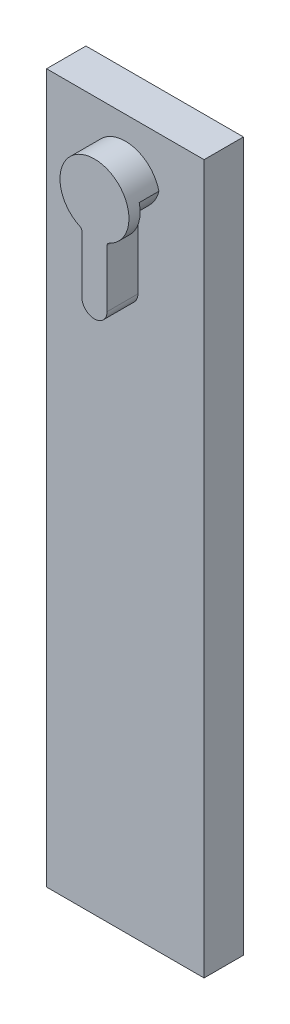
SolidWorks part; units mm, degrees
material "ASA"
ref_plane "Front Plane" through (0, 0, 0) normal (0, 0, 1) x (1, 0, 0)
ref_plane "Top Plane" through (0, 0, 0) normal (0, 1, 0) x (1, 0, 0)
ref_plane "Right Plane" through (0, 0, 0) normal (1, 0, 0) x (0, 0, -1)
sketch "Sketch1" plane through (0, 0, 0) normal (0, 0, 1) x (1, 0, 0)
  line L1 (0, 0) -> (25.4, 0)
  line L2 (0, 0) -> (0, 114.3)
  line L3 (0, 114.3) -> (25.4, 114.3)
  line L4 (25.4, 0) -> (25.4, 114.3)
  dimension "D1" = 25.4
  dimension "D2" = 114.3
extrude "Boss-Extrude1" add sketch "Sketch1" against normal blind 6.35
sketch "Sketch2" plane through (0, 0, 0) normal (0, 0, 1) x (1, 0, 0)
  line L0 (25.4, 114.3) -> (0, 114.3) construction
  line L1 (0, 114.3) -> (0, 0) construction
  circle A0 centre (12.7, 107.5182) radius 5.5626
  circle A1 centre (12.7, 107.5182) radius 6.0706 construction
  dimension "D3" = 0.508
  dimension "D4" = 12.1412
  dimension "D1" = 6.7818
  dimension "D2" = 12.7
extrude "Boss-Extrude2" add sketch "Sketch2" along normal blind 3.175
sketch "Sketch3" plane through (0, 0, 3.175) normal (0, 0, 1) x (1, 0, 0)
  line L0 (12.7, 107.5182) -> (12.7, 104.9782) construction
  circle A0 centre (12.7, 104.9782) radius 5.5626
  circle A2 centre (12.7, 107.5182) radius 5.5626 construction
  dimension "D1" = 2.54
extrude "Boss-Extrude3" add sketch "Sketch3" along normal blind 1.8
sketch "Sketch4" plane through (0, 0, 0) normal (0, 0, 1) x (1, 0, 0)
  line L0 (12.7, 107.5182) -> (12.7, 90.2208) construction
  line L1 (15.24, 107.5182) -> (15.24, 90.2208) construction
  line L2 (10.16, 107.5182) -> (10.16, 90.2208) construction
  line L3 (14.732, 107.5182) -> (14.732, 90.2208)
  line L4 (10.668, 107.5182) -> (10.668, 90.2208)
  arc A0 (15.24, 107.5182) -> (10.16, 107.5182) centre (12.7, 107.5182) ccw construction
  arc A1 (10.16, 90.2208) -> (15.24, 90.2208) centre (12.7, 90.2208) ccw construction
  circle A2 centre (12.7, 107.5182) radius 5.5626 construction
  arc A3 (10.668, 90.2208) -> (14.732, 90.2208) centre (12.7, 90.2208) ccw
  arc A4 (14.732, 107.5182) -> (10.668, 107.5182) centre (12.7, 107.5182) ccw
  point P2 (12.7, 98.8695)
  dimension "D2" = 25.4
  dimension "D1" = 5.08
  dimension "D3" = 0.508
extrude "Boss-Extrude4" add sketch "Sketch4" along normal up to surface (4.975 mm away) up to face at (18.2626, 104.9782, 4.975)
sketch "Sketch5" plane through (0, 0, 4.975) normal (0, 0, 1) x (1, 0, 0)
  line L0 (7.1374, 114.3) -> (7.1374, 104.9782)
  line L1 (18.2626, 104.9782) -> (18.2626, 114.3)
  line L2 (18.2626, 114.3) -> (7.1374, 114.3)
  line L3 (25.4, 114.3) -> (0, 114.3) construction
  arc A0 (7.1374, 104.9782) -> (18.2626, 104.9782) centre (12.7, 104.9782) cw
  arc A1 (14.732, 99.8) -> (10.668, 99.8) centre (12.7, 104.9782) ccw construction
extrude "Cut-Extrude1" cut sketch "Sketch5" against normal up to surface (4.975 mm away) up to face at (12.7, 57.15, 0)
fillet "Fillet1" radius 0.508 4 edges at (10.668, 99.8, 4.075) (10.668, 102.34, 1.5875) (14.732, 99.8, 4.075) (14.732, 102.34, 1.5875)
equation "\"D1@Boss-Extrude3\"=1.8mm"
